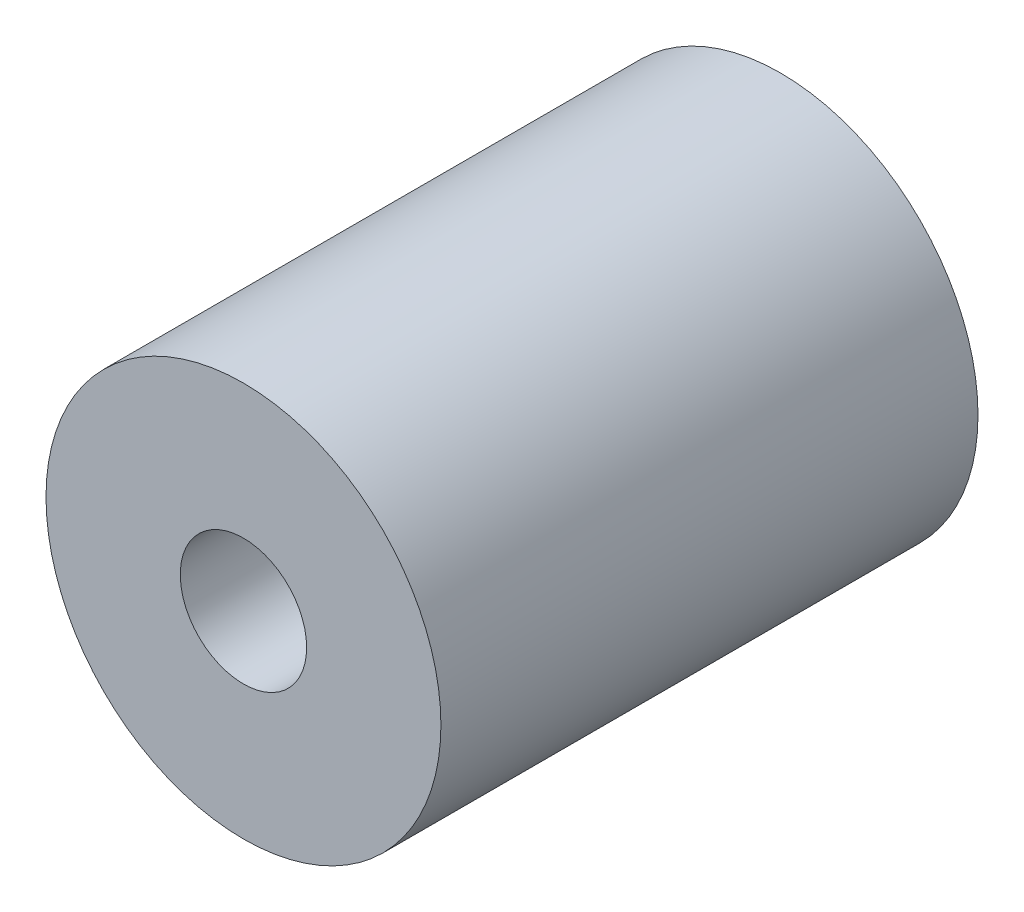
SolidWorks part; units mm, degrees
material "3.3535 (EN-AW 5754)"
ref_plane "Ebene vorne" through (0, 0, 0) normal (0, 0, 1) x (1, 0, 0)
ref_plane "Ebene oben" through (0, 0, 0) normal (0, 1, 0) x (1, 0, 0)
ref_plane "Ebene rechts" through (0, 0, 0) normal (1, 0, 0) x (0, 0, -1)
sketch "Skizze1" plane through (0, 0, 0) normal (0, 0, 1) x (1, 0, 0)
  circle A0 centre (0, 0) radius 12.5
  dimension "D1" = 25
extrude "Aufsatz-Linear austragen1" add sketch "Skizze1" along normal blind 34
sketch "Skizze2" plane through (0, 0, 34) normal (0, 0, 1) x (1, 0, 0)
  circle A0 centre (0, 0) radius 4
  dimension "D1" = 8
extrude "Schnitt-Linear austragen1" cut sketch "Skizze2" against normal blind 12
sketch "Skizze3" plane through (0, 0, 0) normal (0, 0, -1) x (-1, 0, 0)
  circle A0 centre (0, 0) radius 4
  dimension "D1" = 8
extrude "Schnitt-Linear austragen2" cut sketch "Skizze3" against normal blind 12
